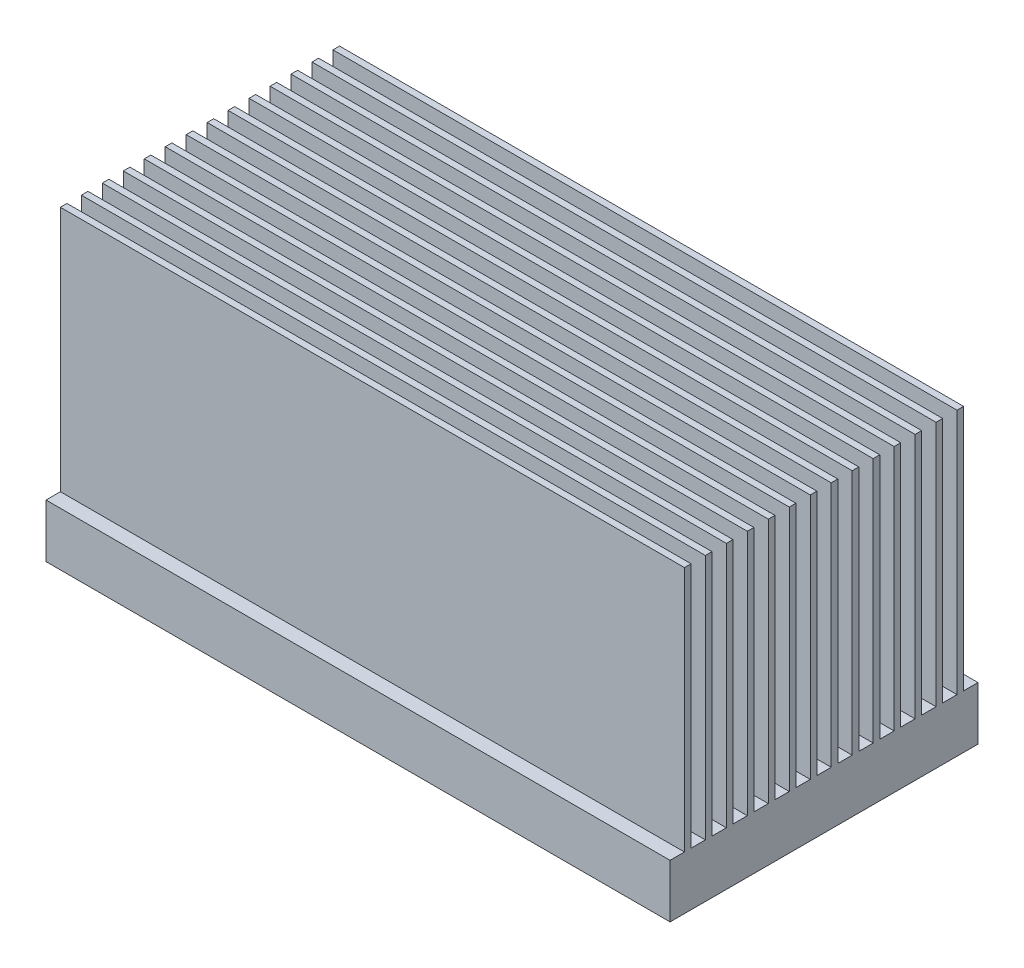
SolidWorks part; units mm, degrees
ref_plane "Front Plane" through (0, 0, 0) normal (0, 0, 1) x (1, 0, 0)
ref_plane "Top Plane" through (0, 0, 0) normal (0, 1, 0) x (1, 0, 0)
ref_plane "Right Plane" through (0, 0, 0) normal (1, 0, 0) x (0, 0, -1)
sketch "Sketch1" plane through (0, 0, 0) normal (0, 1, 0) x (1, 0, 0)
  line L1 (0, 0) -> (152, 0)
  line L2 (0, 0) -> (0, 75)
  line L3 (0, 75) -> (152, 75)
  line L4 (152, 0) -> (152, 75)
  dimension "D1" = 75
  dimension "D2" = 152
extrude "Boss-Extrude1" add sketch "Sketch1" along normal blind 73
sketch "Sketch2" plane through (0, 73, 0) normal (0, 1, 0) x (1, 0, 0)
  line L0 (152, 0) -> (152, 75) construction
  line L1 (0, 0) -> (152, 0)
  line L2 (0, 0) -> (0, 3.5)
  line L3 (0, 3.5) -> (152, 3.5)
  line L4 (152, 0) -> (152, 3.5)
  line L5 (0, 5.1071) -> (0, 8.6071)
  line L6 (0, 5.1071) -> (152, 5.1071)
  line L7 (152, 5.1071) -> (152, 8.6071)
  line L8 (0, 8.6071) -> (152, 8.6071)
  line L9 (0, 10.2143) -> (0, 13.7143)
  line L10 (0, 10.2143) -> (152, 10.2143)
  line L11 (152, 10.2143) -> (152, 13.7143)
  line L12 (0, 13.7143) -> (152, 13.7143)
  line L13 (0, 15.3214) -> (0, 18.8214)
  line L14 (0, 15.3214) -> (152, 15.3214)
  line L15 (152, 15.3214) -> (152, 18.8214)
  line L16 (0, 18.8214) -> (152, 18.8214)
  line L17 (0, 20.4286) -> (0, 23.9286)
  line L18 (0, 20.4286) -> (152, 20.4286)
  line L19 (152, 20.4286) -> (152, 23.9286)
  line L20 (0, 23.9286) -> (152, 23.9286)
  line L21 (0, 25.5357) -> (0, 29.0357)
  line L22 (0, 25.5357) -> (152, 25.5357)
  line L23 (152, 25.5357) -> (152, 29.0357)
  line L24 (0, 29.0357) -> (152, 29.0357)
  line L25 (0, 30.6429) -> (0, 34.1429)
  line L26 (0, 30.6429) -> (152, 30.6429)
  line L27 (152, 30.6429) -> (152, 34.1429)
  line L28 (0, 34.1429) -> (152, 34.1429)
  line L29 (0, 35.75) -> (0, 39.25)
  line L30 (0, 35.75) -> (152, 35.75)
  line L31 (152, 35.75) -> (152, 39.25)
  line L32 (0, 39.25) -> (152, 39.25)
  line L33 (0, 40.8571) -> (0, 44.3571)
  line L34 (0, 40.8571) -> (152, 40.8571)
  line L35 (152, 40.8571) -> (152, 44.3571)
  line L36 (0, 44.3571) -> (152, 44.3571)
  line L37 (0, 45.9643) -> (0, 49.4643)
  line L38 (0, 45.9643) -> (152, 45.9643)
  line L39 (152, 45.9643) -> (152, 49.4643)
  line L40 (0, 49.4643) -> (152, 49.4643)
  line L41 (0, 51.0714) -> (0, 54.5714)
  line L42 (0, 51.0714) -> (152, 51.0714)
  line L43 (152, 51.0714) -> (152, 54.5714)
  line L44 (0, 54.5714) -> (152, 54.5714)
  line L45 (0, 56.1786) -> (0, 59.6786)
  line L46 (0, 56.1786) -> (152, 56.1786)
  line L47 (152, 56.1786) -> (152, 59.6786)
  line L48 (0, 59.6786) -> (152, 59.6786)
  line L49 (0, 61.2857) -> (0, 64.7857)
  line L50 (0, 61.2857) -> (152, 61.2857)
  line L51 (152, 61.2857) -> (152, 64.7857)
  line L52 (0, 64.7857) -> (152, 64.7857)
  line L53 (0, 66.3929) -> (0, 69.8929)
  line L54 (0, 66.3929) -> (152, 66.3929)
  line L55 (152, 66.3929) -> (152, 69.8929)
  line L56 (0, 69.8929) -> (152, 69.8929)
  line L57 (0, 71.5) -> (0, 75)
  line L58 (0, 71.5) -> (152, 71.5)
  line L59 (152, 71.5) -> (152, 75)
  line L60 (0, 75) -> (152, 75)
  line L61 (152, 75) -> (0, 75) construction
  point P7 (152, 75)
  dimension "D1" = 3.5
  dimension "D2" = 15
extrude "Cut-Extrude1" cut sketch "Sketch2" against normal blind 60
